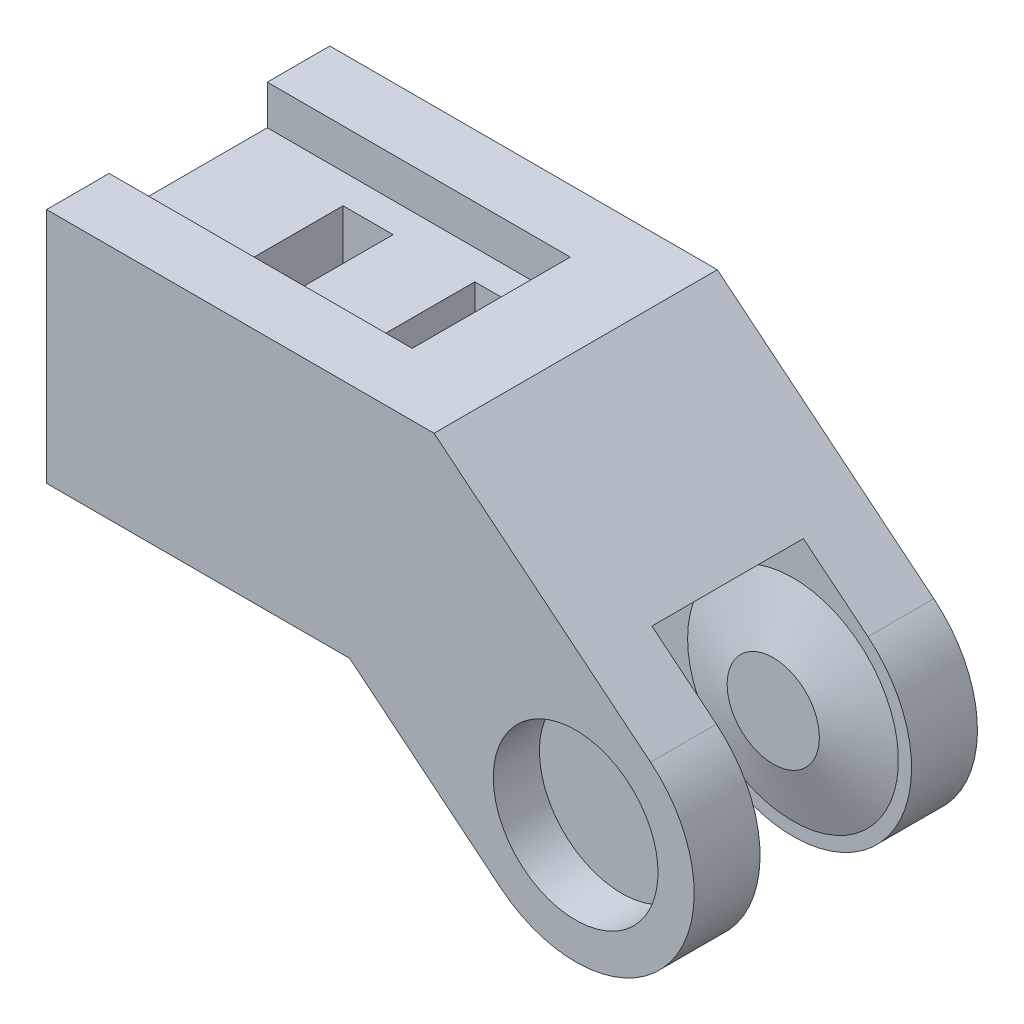
SolidWorks part; units mm, degrees
ref_plane "Front Plane" through (0, 0, 0) normal (0, 0, 1) x (1, 0, 0)
ref_plane "Top Plane" through (0, 0, 0) normal (0, 1, 0) x (1, 0, 0)
ref_plane "Right Plane" through (0, 0, 0) normal (1, 0, 0) x (0, 0, -1)
sketch "Sketch1" plane through (0, 0, 0) normal (0, 0, 1) x (1, 0, 0)
  line L0 (-40.1551, -0.8363) -> (-17.1551, -0.8363)
  line L1 (-17.1551, -0.8363) -> (-5.6892, -10.1902)
  line L2 (-40.1551, -0.8363) -> (-40.1551, 17.1637)
  line L3 (-40.1551, 17.1637) -> (-10.7442, 17.1637)
  line L4 (-10.7442, 17.1637) -> (5.6892, 3.7572)
  line L5 (-5.6892, -10.1902) -> (5.6892, 3.7572) construction
  arc A1 (-5.6892, -10.1902) -> (5.6892, 3.7572) centre (0, -3.2165) ccw
  point P12 (0, 0)
  point P13 (6.4468, 2.8108)
  point P14 (0, 0)
  point P16 (0, -3.2165)
  dimension "D3" = 23
  dimension "D1" = 18
  dimension "D2" = 18
extrude "Boss-Extrude1" add sketch "Sketch1" along normal blind 5
sketch "Sketch8" plane through (0, 0, 5) normal (0, 0, 1) x (1, 0, 0)
  circle A1 centre (0, -3.2165) radius 3.5
  dimension "D1" = 7
extrude "Boss-Extrude5" add sketch "Sketch8" along normal blind 1.5
sketch "Sketch10" plane through (0, 0, 5) normal (0, 0, 1) x (1, 0, 0)
  circle A0 centre (0, -3.2165) radius 8
loft "Loft4" add profiles "Sketch10" section "Sketch10" section face at (3.5, -3.2165, 6.5)
sketch "Sketch14" plane through (0, 0, 5) normal (0, 0, 1) x (1, 0, 0)
  line L0 (-40.1551, -0.8363) -> (-40.1551, 17.1637)
  line L1 (-40.1551, 17.1637) -> (-10.7442, 17.1637)
  line L2 (-10.5899, -6.1923) -> (-17.1551, -0.8363)
  line L3 (-10.7442, 17.1637) -> (-40.1551, 17.1637) construction
  line L4 (5.6892, 3.7572) -> (-10.7442, 17.1637) construction
  line L7 (-17.1551, -0.8363) -> (-40.1551, -0.8363)
  line L8 (-10.7442, 17.1637) -> (0.7886, 7.7552)
  arc A0 (0.7886, 7.7552) -> (-10.5899, -6.1923) centre (0, -3.2165) ccw
  arc A1 (-5.6892, -10.1902) -> (5.6892, 3.7572) centre (0, -3.2165) ccw construction
  point P7 (-12.5318, 17.1637)
  point P12 (-12.5318, 17.1637)
  point P19 (0.7418, 7.7933)
  point P22 (-10.7442, 17.1637)
  dimension "D1" = 11
extrude "Boss-Extrude7" add sketch "Sketch14" along normal blind 5.75 contours A0 L2 L7 L0 L1 L8
sketch "Sketch15" plane through (0, 0, 0) normal (0, 0, -1) x (-1, 0, 0)
  circle A0 centre (0, -3.2165) radius 2.8
  arc A1 (-5.6892, 3.7572) -> (5.6892, -10.1902) centre (0, -3.2165) ccw construction
  dimension "D1" = 5.6
extrude "Cut-Extrude7" cut sketch "Sketch15" against normal blind 10
mirror "Mirror1" about plane through (0, -3.2165, 10.75) normal (0, 0, 1) of bodies 117 114
sketch "Sketch6" plane through (0, 0, 5) normal (0, 0, 1) x (1, 0, 0)
  line L1 (4.2, 0.9835) -> (-4.2, 0.9835)
  line L2 (4.2, 0.9835) -> (4.2, -7.4165)
  line L3 (4.2, -7.4165) -> (-4.2, -7.4165)
  line L4 (-4.2, 0.9835) -> (-4.2, -7.4165)
  line L5 (4.2, 0.9835) -> (-4.2, -7.4165) construction
  line L6 (4.2, -7.4165) -> (-4.2, 0.9835) construction
  point P0 (0, -3.2165)
  dimension "D1" = 8.4
extrude "nut-cut" cut sketch "Sketch6" against normal through all from offset 1.5 offset against normal yes
sketch "Sketch16" plane through (-40.1551, 0, 0) normal (-1, 0, 0) x (0, 0, 1)
  line L0 (21.5, -0.8363) -> (0, -0.8363) construction
  line L1 (4.75, -0.8363) -> (16.75, -0.8363)
  line L2 (4.75, -0.8363) -> (4.75, 2.1637)
  line L3 (4.75, 2.1637) -> (16.75, 2.1637)
  line L4 (16.75, -0.8363) -> (16.75, 2.1637)
  line L6 (21.5, 17.1637) -> (0, 17.1637) construction
  line L8 (16.75, 17.1637) -> (4.75, 17.1637)
  line L9 (16.75, 17.1637) -> (16.75, 14.1637)
  line L11 (16.75, 14.1637) -> (4.75, 14.1637)
  line L12 (4.75, 17.1637) -> (4.75, 14.1637)
  point P7 (10.75, 17.1637)
  dimension "D1" = 12
  dimension "D2" = 3
extrude "Cut-Extrude8" cut sketch "Sketch16" against normal blind 23
sketch "Sketch17" plane through (-40.1551, 0, 0) normal (-1, 0, 0) x (0, 0, 1)
  line L0 (21.5, -0.8363) -> (16.75, -0.8363) construction
  line L1 (21.5, 17.1637) -> (21.5, -0.8363) construction
  circle A0 centre (10.75, 8.1637) radius 2.35
  point P4 (19.125, 8.1637)
  point P6 (0, 0)
  dimension "D1" = 4.7
  dimension "D2" = 9
  dimension "D3" = 10.75
extrude "Cut-Extrude9" cut sketch "Sketch17" against normal blind 28
sketch "Sketch19" plane through (0, 0, 16.5) normal (0, 0, 1) x (1, 0, 0)
  circle A0 centre (0, -3.2165) radius 6.25
  dimension "D1" = 12.5
extrude "Cut-Extrude10" cut sketch "Sketch19" along normal through all from offset 1.5
sketch "Sketch20" plane through (-40.1551, 0, 0) normal (-1, 0, 0) x (0, 0, 1)
  line L0 (7, 14.1637) -> (14.5, 14.1637)
  line L1 (10.75, 3.8336) -> (14.5, 5.9987)
  line L2 (14.5, 5.9987) -> (14.5, 14.1637)
  line L3 (14.5, 10.3288) -> (10.75, 12.4939) construction
  line L4 (10.75, 12.4939) -> (7, 10.3288) construction
  line L5 (7, 14.1637) -> (7, 5.9987)
  line L6 (7, 5.9987) -> (10.75, 3.8336)
  line L7 (4.75, 14.1637) -> (16.75, 14.1637) construction
  line L8 (4.75, 14.1637) -> (16.75, 14.1637) construction
  line L9 (7, 14.1637) -> (14.5, 14.1637)
  line L10 (14.5, 14.1637) -> (14.4669, 14.1279)
  circle A0 centre (10.75, 8.1637) radius 3.75 construction
  point P15 (19.125, 8.1637)
  dimension "D1" = 7.5
extrude "Cut-Extrude11" cut sketch "Sketch20" against normal blind 3.8 from offset 8 offset against normal yes
pattern_linear "LPattern1" count 2 spacing 10 along (1, 0, 0) of "Cut-Extrude11"
sketch "Sketch22" plane through (0, 0, 6.5) normal (0, 0, -1) x (-1, 0, 0)
  circle A0 centre (0, -3.2165) radius 3.0518
extrude "Boss-Extrude8" add sketch "Sketch22" along normal blind 0.65
sketch "Sketch23" plane through (0, 0, 18) normal (0, 0, 1) x (1, 0, 0)
  circle A0 centre (0, -3.2165) radius 3.919
extrude "Boss-Extrude9" add sketch "Sketch23" against normal blind 0.65
